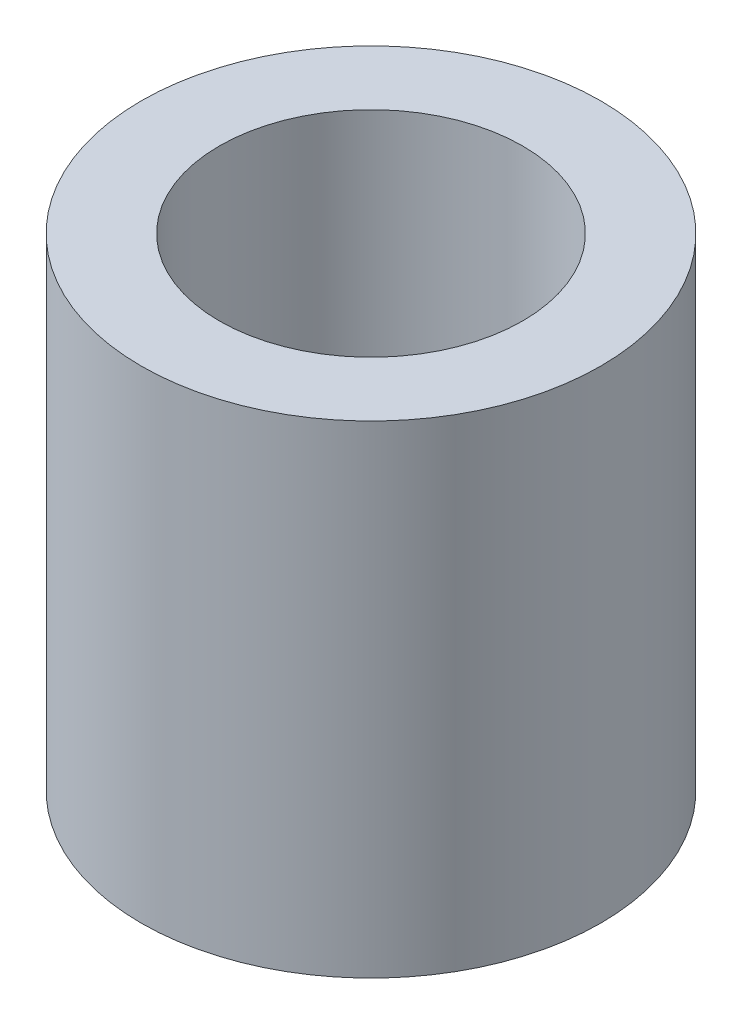
SolidWorks part; units mm, degrees
ref_plane "Front Plane" through (0, 0, 0) normal (0, 0, 1) x (1, 0, 0)
ref_plane "Top Plane" through (0, 0, 0) normal (0, 1, 0) x (1, 0, 0)
ref_plane "Right Plane" through (0, 0, 0) normal (1, 0, 0) x (0, 0, -1)
sketch "Sketch1" plane through (0, 0, 0) normal (0, 1, 0) x (1, 0, 0)
  circle A0 centre (0, 0) radius 1.65
  circle A1 centre (0, 0) radius 2.5
  dimension "D1" = 3.3
  dimension "D2" = 5
extrude "Boss-Extrude1" add sketch "Sketch1" along normal blind 5.25
